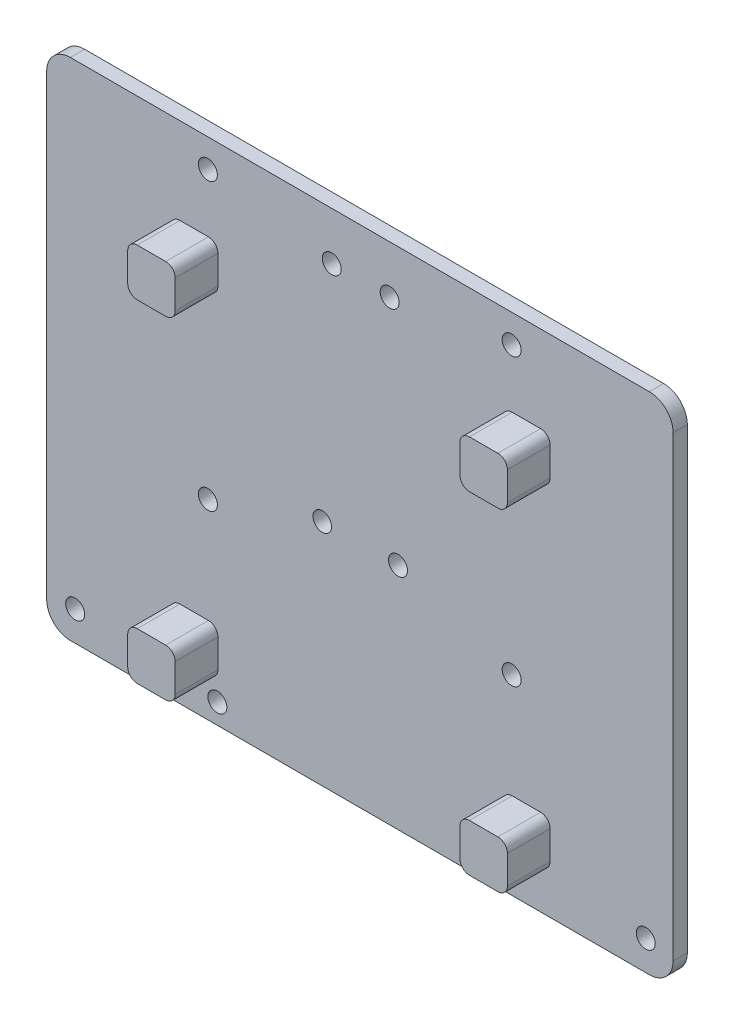
SolidWorks part; units mm, degrees
ref_plane "Front Plane" through (0, 0, 0) normal (0, 0, 1) x (1, 0, 0)
ref_plane "Top Plane" through (0, 0, 0) normal (0, 1, 0) x (1, 0, 0)
ref_plane "Right Plane" through (0, 0, 0) normal (1, 0, 0) x (0, 0, -1)
other "Graphic1"
other "object_1 (Open) -1"
ref_plane "Plane1" through (0, 0, 10) normal (0, 0, 1) x (1, 0, 0)
sketch "Sketch1" plane through (0, 0, 10) normal (0, 0, 1) x (1, 0, 0)
  line L1 (144.9639, 320.0391) -> (210.9639, 320.0391)
  line L2 (144.9639, 320.0391) -> (144.9639, 266.8391)
  line L3 (144.9639, 266.8391) -> (210.9639, 266.8391)
  line L4 (210.9639, 320.0391) -> (210.9639, 266.8391)
  circle A0 centre (161.9475, 317.0605) radius 1
  circle A1 centre (193.9565, 317.0605) radius 1
  circle A2 centre (174.9978, 314.9828) radius 1
  circle A3 centre (181.1009, 314.9828) radius 1
  circle A4 centre (173.9978, 290.9653) radius 0.9833
  circle A5 centre (181.9833, 290.9653) radius 1
  circle A6 centre (161.9475, 286.9627) radius 1
  circle A7 centre (193.9565, 286.9627) radius 1
  circle A8 centre (162.9475, 268.9705) radius 1
  circle A9 centre (192.9565, 268.9705) radius 1.0113
  circle A10 centre (208.0846, 269.9818) radius 1
  circle A11 centre (147.9666, 269.9705) radius 1
  dimension "D1" = 66
  dimension "D2" = 53.2
extrude "Boss-Extrude1" add sketch "Sketch1" along normal blind 1.5
sketch "Sketch2" plane through (0, 0, 11.5) normal (0, 0, 1) x (1, 0, 0)
  line L0 (193.0042, 310.9393) -> (193.0042, 305.9393)
  line L1 (158.0042, 310.9393) -> (163.0042, 310.9393)
  line L2 (158.0042, 310.9393) -> (158.0042, 305.9393)
  line L3 (158.0042, 305.9393) -> (163.0042, 305.9393)
  line L4 (163.0042, 310.9393) -> (163.0042, 305.9393)
  line L5 (193.0042, 310.9393) -> (198.0042, 310.9393)
  line L6 (198.0042, 310.9393) -> (198.0042, 305.9393)
  line L7 (193.0042, 305.9393) -> (198.0042, 305.9393)
  line L8 (193.0042, 275.9393) -> (193.0042, 270.9393)
  line L9 (193.0042, 275.9393) -> (198.0042, 275.9393)
  line L10 (198.0042, 275.9393) -> (198.0042, 270.9393)
  line L11 (193.0042, 270.9393) -> (198.0042, 270.9393)
  line L12 (158.0042, 275.9393) -> (158.0042, 270.9393)
  line L13 (158.0042, 275.9393) -> (163.0042, 275.9393)
  line L14 (163.0042, 275.9393) -> (163.0042, 270.9393)
  line L15 (158.0042, 270.9393) -> (163.0042, 270.9393)
  dimension "D1" = 5
  dimension "D2" = 5
  dimension "D3" = 2
  dimension "D4" = 2
extrude "Boss-Extrude2" add sketch "Sketch2" along normal blind 4.5
fillet "Fillet1" radius 1 16 edges at (158.0042, 275.9393, 13.75) (163.0042, 275.9393, 13.75) (163.0042, 270.9393, 13.75) (158.0042, 270.9393, 13.75) (198.0042, 275.9393, 13.75) (193.0042, 275.9393, 13.75) (198.0042, 270.9393, 13.75) (193.0042, 270.9393, 13.75) (193.0042, 305.9393, 13.75) (193.0042, 310.9393, 13.75) (198.0042, 305.9393, 13.75) (198.0042, 310.9393, 13.75) (158.0042, 310.9393, 13.75) (163.0042, 310.9393, 13.75) (163.0042, 305.9393, 13.75) (158.0042, 305.9393, 13.75)
fillet "Fillet2" radius 2.5 4 edges at (144.9639, 320.0391, 10.75) (210.9639, 320.0391, 10.75) (210.9639, 266.8391, 10.75) (144.9639, 266.8391, 10.75)
